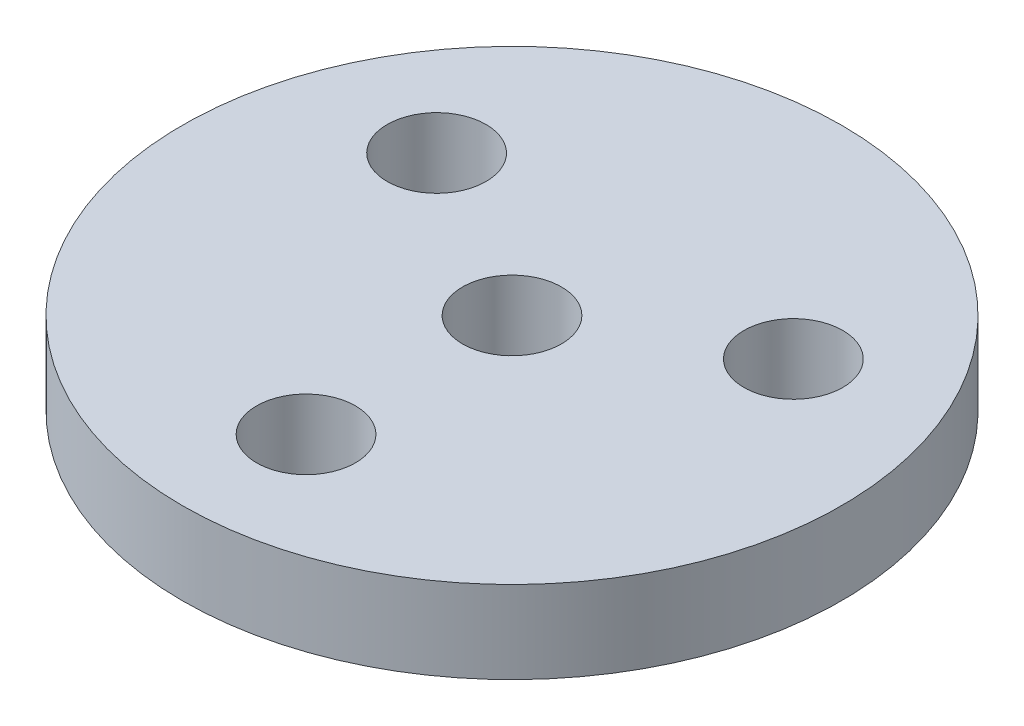
SolidWorks part; units mm, degrees
other "标注1"
sketch "草图3" plane through (-22.25, 4, -10) normal (-0.231, 0.6469, -0.7268) x (-0.9696, -0.2151, 0.1167)
ref_plane "前视基准面" through (0, 0, 0) normal (0, 0, 1) x (1, 0, 0)
ref_plane "上视基准面" through (0, 0, 0) normal (0, 1, 0) x (1, 0, 0)
ref_plane "右视基准面" through (0, 0, 0) normal (1, 0, 0) x (0, 0, -1)
other "Configuration Table"
sketch "草图4" plane through (0, 0, 0) normal (0, 1, 0) x (1, 0, 0)
  circle A0 centre (0, 0) radius 8
  circle A1 centre (0, 0) radius 1.2
  dimension "D1" = 16
  dimension "D2" = 2.4
extrude "凸台-拉伸1" add sketch "草图4" along normal blind 2 contours A0 | A1
sketch "草图5" plane through (0, 0, 0) normal (0, -1, 0) x (1, 0, 0)
  circle A0 centre (0, 5) radius 1.2
  point P2 (0, 0)
  point P6 (1.6894, 4.7059)
  dimension "D1" = 2.4
  dimension "D2" = 5
extrude "切除-拉伸1" cut sketch "草图5" against normal through all
pattern_circular "阵列(圆周)1" count 3 over 360 about axis through (0, 0, 0) along (0, 1, 0) of "切除-拉伸1"
